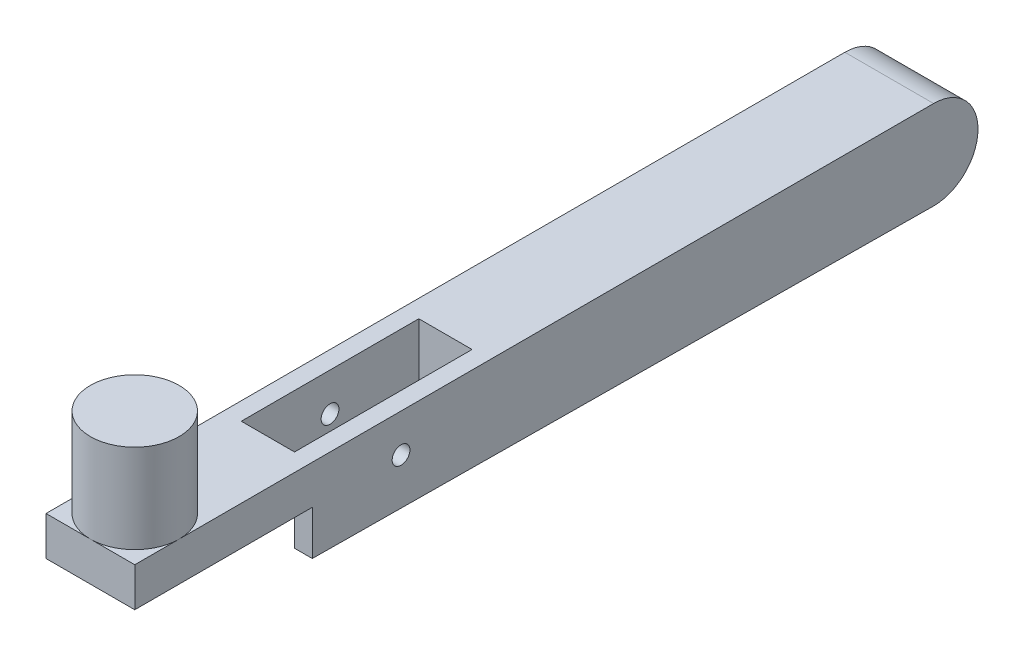
SolidWorks part; units mm, degrees
ref_plane "Front Plane" through (0, 0, 0) normal (0, 0, 1) x (1, 0, 0)
ref_plane "Top Plane" through (0, 0, 0) normal (0, 1, 0) x (1, 0, 0)
ref_plane "Right Plane" through (0, 0, 0) normal (1, 0, 0) x (0, 0, -1)
sketch "Sketch1" plane through (0, 0, 0) normal (1, 0, 0) x (0, 0, -1)
  line L0 (-209.8883, 35.419) -> (140.1117, 35.419)
  line L5 (140.1117, 35.419) -> (140.1117, -14.581)
  line L6 (140.1117, -14.581) -> (-209.8883, -11.5642)
  line L7 (-209.8883, -11.5642) -> (-209.8883, 13.4358)
  line L8 (-209.8883, 13.4358) -> (-309.8883, 13.4358)
  line L9 (-309.8883, 13.4358) -> (-309.8883, 35.419)
  line L10 (-309.8883, 35.419) -> (-209.8883, 35.419)
  circle A0 centre (140.1117, 10.419) radius 25
  dimension "D1" = 350
  dimension "D2" = 25
  dimension "D3" = 50
  dimension "D4" = 100
extrude "Boss-Extrude1" add sketch "Sketch1" along normal blind 50 contours A0 L0 L10 L9 L8 L7 L6 | L5 A0 L6 | L5 A0
sketch "Sketch2" plane through (0, 0, 0) normal (0, 1, 0) x (1, 0, 0)
  line L0 (50, -309.8883) -> (0, -309.8883) construction
  line L2 (0, -309.8883) -> (0, 140.1117) construction
  circle A0 centre (25, -284.8883) radius 25
  point P6 (0, -255.2457)
  dimension "D1" = 50
  dimension "D2" = 25
  dimension "D3" = 25
extrude "Boss-Extrude2" add sketch "Sketch2" along normal blind 50 from surface at 35.419 starting at face at (25, 35.419, 84.8883)
sketch "Sketch4" plane through (0, 35.419, 0) normal (0, 1, 0) x (1, 0, 0)
  line L1 (10, -109.8883) -> (40, -109.8883)
  line L2 (10, -109.8883) -> (10, -209.8883)
  line L3 (10, -209.8883) -> (40, -209.8883)
  line L4 (40, -109.8883) -> (40, -209.8883)
  line L7 (0, -284.8883) -> (0, 140.1117) construction
  dimension "D1" = 10
  dimension "D2" = 30
  dimension "D3" = 100
extrude "Cut-Extrude1" cut sketch "Sketch4" against normal through all
sketch "Sketch5" plane through (50, 0, 0) normal (1, 0, 0) x (0, 0, -1)
  line L0 (-209.8883, -11.5642) -> (-209.8883, 13.4358) construction
  circle A0 centre (-159.8883, 13.9451) radius 5
  dimension "D1" = 10
  dimension "D2" = 50
extrude "Cut-Extrude2" cut sketch "Sketch5" against normal through all
